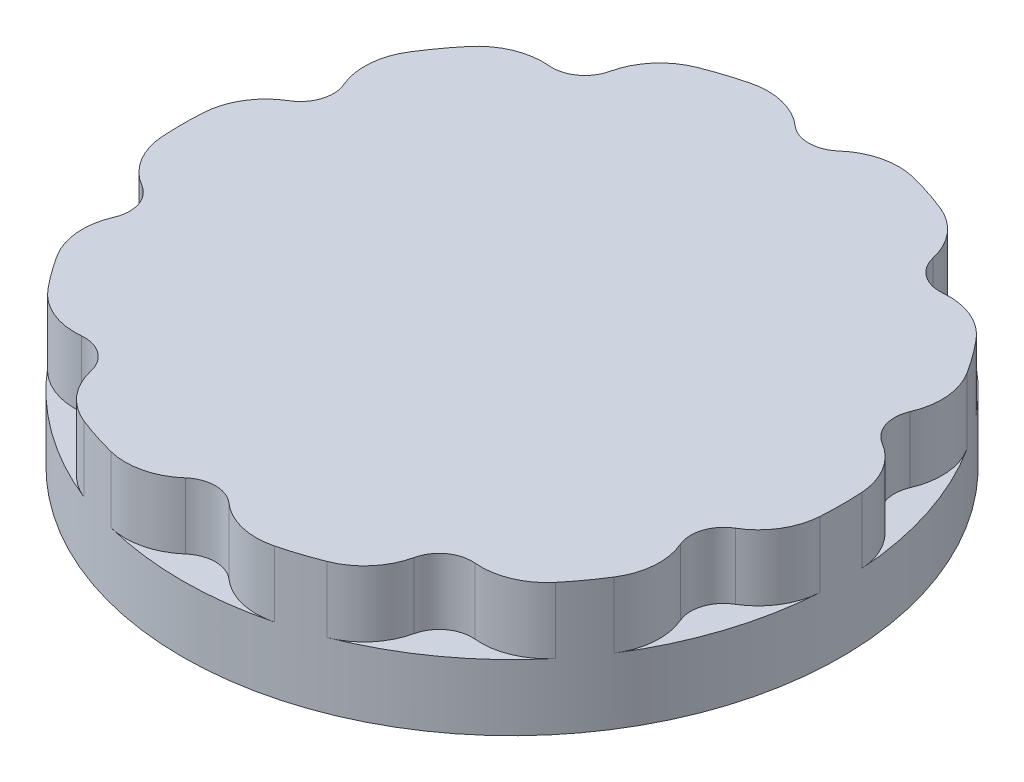
SolidWorks part; units mm, degrees
ref_plane "Front Plane" through (0, 0, 0) normal (0, 0, 1) x (1, 0, 0)
ref_plane "Top Plane" through (0, 0, 0) normal (0, 1, 0) x (1, 0, 0)
ref_plane "Right Plane" through (0, 0, 0) normal (1, 0, 0) x (0, 0, -1)
sketch "Sketch1" plane through (0, 0, 0) normal (0, 1, 0) x (1, 0, 0)
  circle A0 centre (0, 0) radius 10
  dimension "D1" = 20
extrude "Boss-Extrude1" add sketch "Sketch1" along normal blind 4
sketch "Sketch2" plane through (0, 4, 0) normal (0, 1, 0) x (1, 0, 0)
  line L0 (0, 0) -> (0, -10) construction
  circle A0 centre (0, -10) radius 1
  circle A1 centre (0, 0) radius 10 construction
  circle A2 centre (-5.8779, -8.0902) radius 1
  circle A3 centre (-9.5106, -3.0902) radius 1
  circle A4 centre (-9.5106, 3.0902) radius 1
  circle A5 centre (-5.8779, 8.0902) radius 1
  circle A6 centre (0, 10) radius 1
  circle A7 centre (5.8779, 8.0902) radius 1
  circle A8 centre (9.5106, 3.0902) radius 1
  circle A9 centre (9.5106, -3.0902) radius 1
  circle A10 centre (5.8779, -8.0902) radius 1
  point P107 (0, 0)
  dimension "D1" = 2
  dimension "D2" = 10
extrude "Cut-Extrude1" cut sketch "Sketch2" against normal blind 2
fillet "Fillet1" radius 2 20 edges at (5.0405, 3, -8.6368) (6.6565, 3, -7.4627) (9.1544, 3, -4.0246) (9.7716, 3, -2.1249) (9.7716, 3, 2.1249) (9.1544, 3, 4.0246) (6.6565, 3, 7.4627) (5.0405, 3, 8.6368) (0.9987, 3, 9.95) (-0.9987, 3, 9.95) (-6.6565, 3, 7.4627) (-5.0405, 3, 8.6368) (-9.1544, 3, 4.0246) (-9.7716, 3, 2.1249) (-9.7716, 3, -2.1249) (-9.1544, 3, -4.0246) (-6.6565, 3, -7.4627) (-5.0405, 3, -8.6368) (-0.9987, 3, -9.95) (0.9987, 3, -9.95)
sketch "Sketch3" plane through (0, 4, 0) normal (0, 1, 0) x (1, 0, 0)
  circle A0 centre (0, 0) radius 7.5
  dimension "D1" = 15
